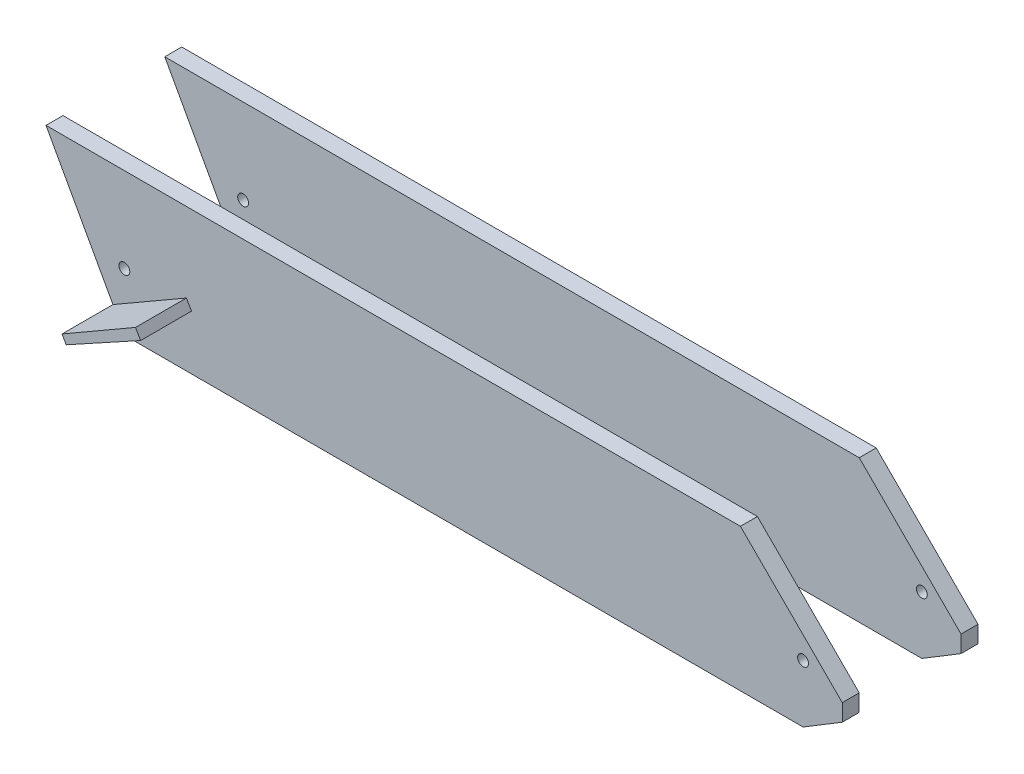
SolidWorks part; units mm, degrees
other "Markup1"
sketch "Sketch17" plane through (-23.09, 0, 55) normal (-0.9942, 0.0102, 0.1066) x (0.1071, 0.0666, 0.992)
ref_plane "Front Plane" through (0, 0, 0) normal (0, 0, 1) x (1, 0, 0)
ref_plane "Top Plane" through (0, 0, 0) normal (0, 1, 0) x (1, 0, 0)
ref_plane "Right Plane" through (0, 0, 0) normal (1, 0, 0) x (0, 0, -1)
sketch "Sketch1" plane through (0, 0, 0) normal (0, 0, 1) x (1, 0, 0)
  line L0 (0, 0) -> (200, 0)
  line L1 (200, 0) -> (200, -42)
  line L2 (200, -42) -> (0, -42)
  line L3 (0, -42) -> (0, 0)
  line L4 (200, 0) -> (269.28, 0)
  line L5 (269.28, 0) -> (200, -42)
  line L6 (0, 0) -> (-23.09, 0)
  line L7 (-23.09, 0) -> (0, -42)
  dimension "D2" = 42
  dimension "D3" = 69.28
extrude "Boss-Extrude1" add sketch "Sketch1" along normal blind 40 contours L5 L4 L1 | L3 L2 L1 L0 | L6 L7 L3
sketch "Sketch2" plane through (0, 0, 0) normal (0, 1, 0) x (1, 0, 0)
  line L0 (-23.09, -5) -> (269.28, -5)
  line L1 (-23.09, -40) -> (-23.09, 0) construction
  line L2 (-23.09, 0) -> (269.28, 0) construction
  line L3 (269.28, -35) -> (-23.09, -35)
  line L4 (269.28, -40) -> (269.28, 0) construction
  line L5 (-23.09, -40) -> (269.28, -40) construction
  point P12 (123.095, -40)
  dimension "D1" = 5
  dimension "D2" = 5
  dimension "D3" = 292.37
  dimension "D4" = 292.37
sketch "Sketch3" plane through (0, 0, 0) normal (0, 1, 0) x (1, 0, 0)
sketch "Sketch5" plane through (0, 0, 0) normal (0, 1, 0) x (1, 0, 0)
  line L0 (-23.09, -5) -> (-23.09, -35)
  line L1 (269.28, -5) -> (269.28, -35)
  dimension "D1" = 30
  dimension "D2" = 30
sketch "Sketch7" plane through (0, 0, 0) normal (0, 1, 0) x (1, 0, 0)
  line L0 (-23.09, -5) -> (269.28, -5)
  line L1 (-23.09, -40) -> (-23.09, 0) construction
  line L2 (269.28, -40) -> (269.28, 0) construction
  line L3 (-23.09, 0) -> (269.28, 0) construction
  line L4 (-23.09, -35) -> (269.28, -35)
  line L5 (-23.09, -40) -> (269.28, -40) construction
  line M4 (-23.09, 0) -> (-23.09, -40)
  line M6 (269.28, -40) -> (269.28, 0)
  dimension "D1" = 5
  dimension "D2" = 30
  dimension "D3" = 5
  dimension "D4" = 5
  dimension "D5" = 292.37
  dimension "D6" = 292.37
sketch "Sketch9" plane through (0, 0, 0) normal (0, 1, 0) x (1, 0, 0)
sketch "Sketch10" plane through (0, 0, 0) normal (0, 1, 0) x (1, 0, 0)
extrude "Cut-Extrude1" cut sketch "Sketch7" against normal blind 35 contours L4 L0 M4 M6
sketch "Sketch11" plane through (0, 0, 40) normal (0, 0, 1) x (1, 0, 0)
  line L0 (0, -42) -> (0, -25)
  line L1 (200, -42) -> (0, -42) construction
  line L2 (-23.09, 0) -> (0, -42) construction
  line L4 (200, -42) -> (200, -25)
  circle A1 centre (0, -25) radius 1.6
  circle A2 centre (200, -25) radius 1.6
  dimension "D3" = 3.2
  dimension "D2" = 3.2
  dimension "D1" = 17
  dimension "D4" = 17
extrude "Cut-Extrude2" cut sketch "Sketch11" against normal blind 60
sketch "Sketch12" plane through (0, 0, 40) normal (0, 0, 1) x (1, 0, 0)
  line L0 (0, -42) -> (-3.3671, -35.8754)
  line L2 (0.8667, -33.4314) -> (-3.3671, -35.8754)
  line L3 (-23.09, 0) -> (0, -42) construction
  line L4 (-3.3671, -35.8754) -> (18.2845, -23.377)
  line L5 (18.2845, -23.377) -> (19.7843, -25.9752)
  line L6 (19.7843, -25.9752) -> (-2.1734, -38.0467)
  line M8 (-23.09, 0) -> (0, -42)
  dimension "D1" = 6.9891
  dimension "D2" = 25
  dimension "D3" = 3
  dimension "D4" = 25
  dimension "D5" = 21.6516
sketch "Sketch14" plane through (0, 0, 40) normal (0, 0, 1) x (1, 0, 0)
extrude "Boss-Extrude3" add sketch "Sketch12" along normal blind 15 contours L6 L5 L4 L2 M8
sketch "Sketch15" plane through (0, -35, 0) normal (0, 1, 0) x (1, 0, 0)
  line L0 (211.5467, -5) -> (211.5467, 0)
  line L1 (-23.09, 0) -> (269.28, 0) construction
  line L2 (211.5467, -5) -> (211.5467, -35)
  line L3 (211.5467, -35) -> (211.5467, -40)
  line L4 (-23.09, -40) -> (269.28, -40) construction
  line L5 (211.5467, -40) -> (269.28, -40)
  line L6 (269.28, -40) -> (269.28, 0)
  line L7 (269.28, 0) -> (211.5467, 0)
extrude "Cut-Extrude3" cut sketch "Sketch15" against normal mid plane 100
sketch "Sketch16" plane through (0, -35, 0) normal (0, 1, 0) x (1, 0, 0)
  line L1 (-3.8483, -5) -> (211.5467, -5)
  line L2 (-3.8483, -5) -> (-3.8483, -35)
  line L3 (-3.8483, -35) -> (211.5467, -35)
  line L4 (211.5467, -5) -> (211.5467, -35)
extrude "Cut-Extrude4" cut sketch "Sketch16" against normal up to next
chamfer "Chamfer1" distance 30 angle 45 1 edges at (211.5467, 0, 37.5)
chamfer "Chamfer2" distance 30 angle 45 1 edges at (211.5467, 0, 2.5)
